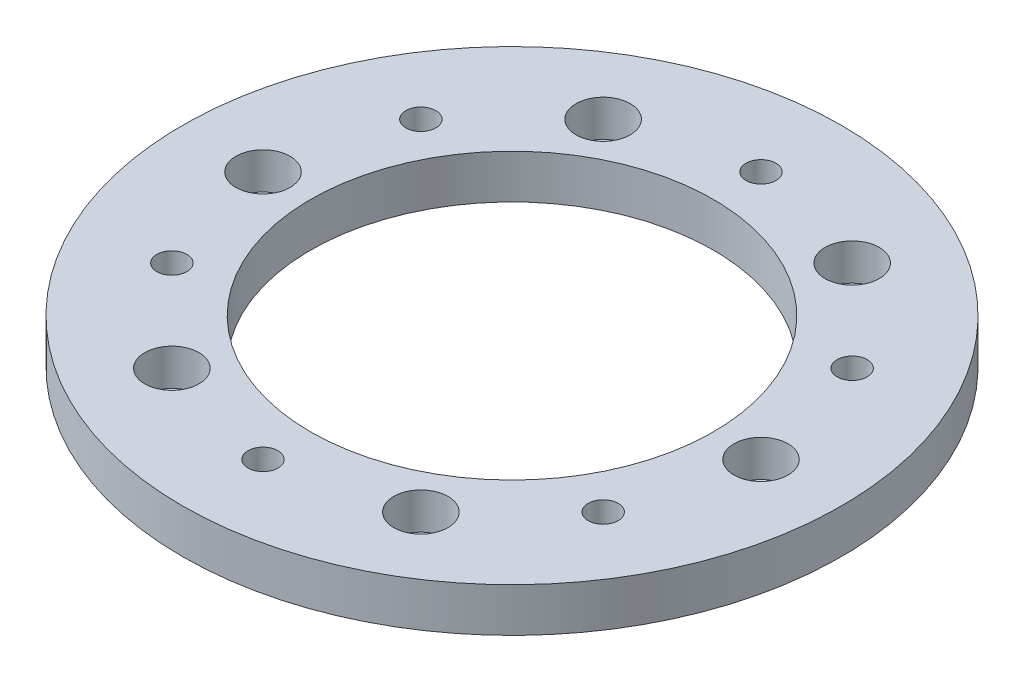
SolidWorks part; units mm, degrees
ref_plane "前视基准面" through (0, 0, 0) normal (0, 0, 1) x (1, 0, 0)
ref_plane "上视基准面" through (0, 0, 0) normal (0, 1, 0) x (1, 0, 0)
ref_plane "右视基准面" through (0, 0, 0) normal (1, 0, 0) x (0, 0, -1)
sketch "草图1" plane through (0, 0, 0) normal (0, 1, 0) x (1, 0, 0)
  circle A0 centre (0, 0) radius 45
  circle A1 centre (34, 0) radius 2.05
  circle A2 centre (29.4449, -17) radius 2.05
  circle A3 centre (17, -29.4449) radius 2.05
  circle A4 centre (0, -34) radius 2.05
  circle A5 centre (-17, -29.4449) radius 2.05
  circle A6 centre (-29.4449, -17) radius 2.05
  circle A7 centre (-34, 0) radius 2.05
  circle A8 centre (-29.4449, 17) radius 2.05
  circle A9 centre (-17, 29.4449) radius 2.05
  circle A10 centre (0, 34) radius 2.05
  circle A11 centre (17, 29.4449) radius 2.05
  circle A12 centre (29.4449, 17) radius 2.05
  circle A13 centre (0, 0) radius 27.5
  point P30 (0, 0)
  dimension "D1" = 90
  dimension "D2" = 4.1
  dimension "D4" = 12
  dimension "D5" = 55
  dimension "D3" = 34
extrude "凸台-拉伸1" add sketch "草图1" along normal blind 6
sketch "草图2" plane through (0, 6, 0) normal (0, 1, 0) x (1, 0, 0)
  circle A0 centre (34, 0) radius 3.7
  circle A1 centre (17, -29.4449) radius 3.7
  circle A2 centre (-17, -29.4449) radius 3.7
  circle A3 centre (-34, 0) radius 3.7
  circle A4 centre (-17, 29.4449) radius 3.7
  circle A5 centre (17, 29.4449) radius 3.7
  point P15 (0, 0)
  dimension "D1" = 7.4
  dimension "D2" = 6
extrude "切除-拉伸1" cut sketch "草图2" against normal blind 5
